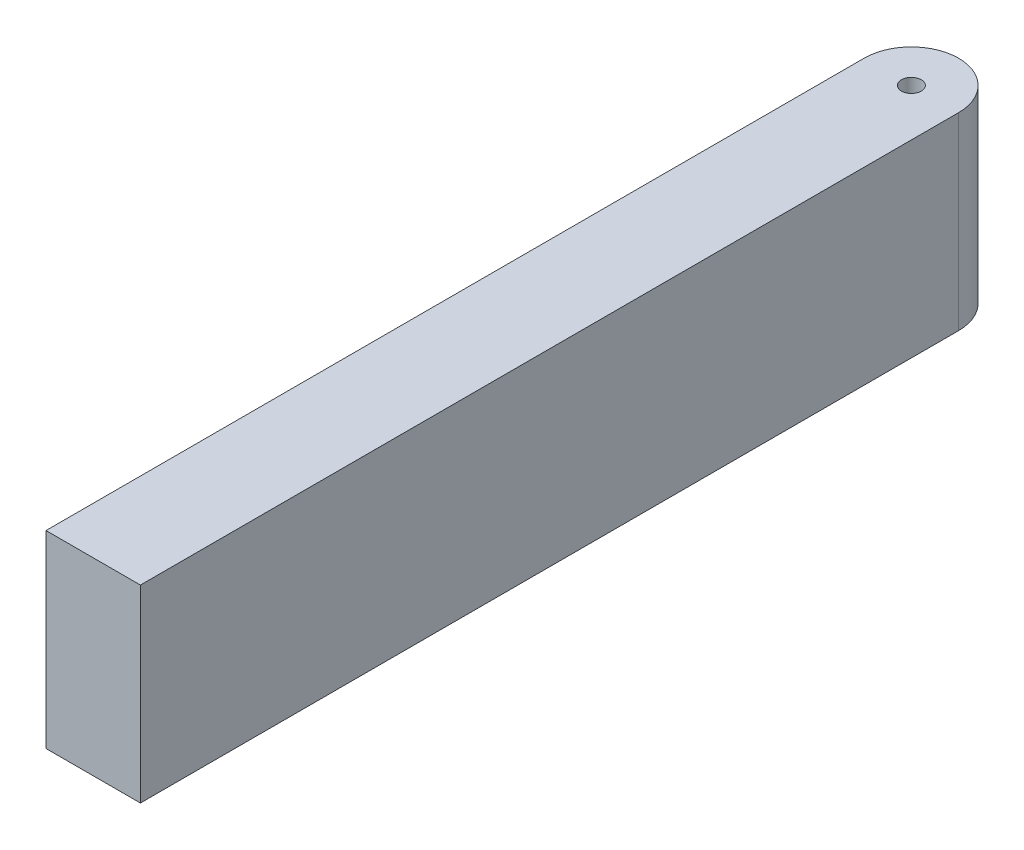
SolidWorks part; units mm, degrees
ref_plane "Front Plane" through (0, 0, 0) normal (0, 0, 1) x (1, 0, 0)
ref_plane "Top Plane" through (0, 0, 0) normal (0, 1, 0) x (1, 0, 0)
ref_plane "Right Plane" through (0, 0, 0) normal (1, 0, 0) x (0, 0, -1)
sketch "Sketch1" plane through (0, 0, 0) normal (0, 0, 1) x (1, 0, 0)
  line L0 (0, 0) -> (19.05, 0)
  line L1 (19.05, 0) -> (19.05, -76.2)
  line L2 (19.05, -76.2) -> (0, -76.2)
  line L3 (0, -76.2) -> (0, 0)
  dimension "D1" = 76.2
  dimension "D2" = 19.05
revolve "Revolve1" add sketch "Sketch1" angle 180 about L1
sketch "Sketch2" plane through (0, 0, 0) normal (0, 0, 1) x (1, 0, 0)
  line L1 (0, 0) -> (38.1, 0)
  line L2 (0, 0) -> (0, -76.2)
  line L3 (0, -76.2) -> (38.1, -76.2)
  line L4 (38.1, 0) -> (38.1, -76.2)
extrude "Boss-Extrude1" add sketch "Sketch2" along normal blind 330.2
sketch "Sketch3" plane through (0, 0, 0) normal (0, 1, 0) x (1, 0, 0)
  line L0 (38.1, 0) -> (0, 0) construction
  arc A0 (38.1, 0) -> (0, 0) centre (19.05, 0) ccw construction
  circle A1 centre (19.05, 0) radius 3.9878
  dimension "D1" = 7.9756
extrude "Cut-Extrude1" cut sketch "Sketch3" against normal through all
